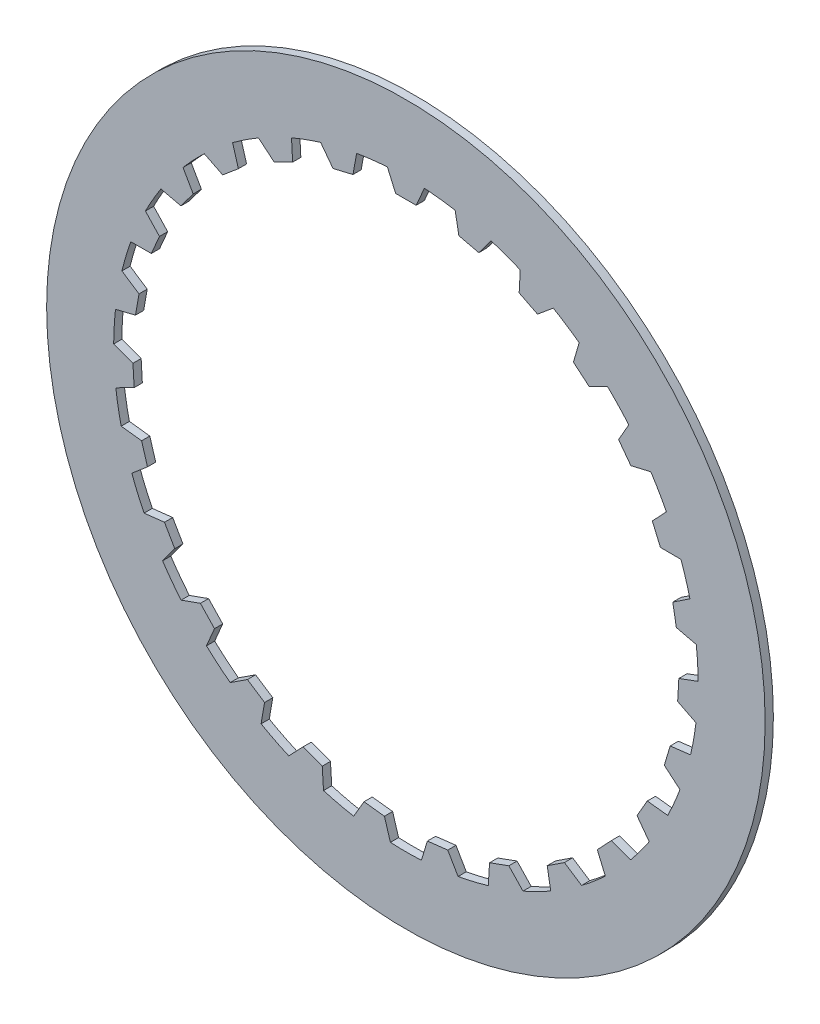
SolidWorks part; units mm, degrees
material "Plain Carbon Steel"
ref_plane "Front Plane" through (0, 0, 0) normal (0, 0, 1) x (1, 0, 0)
ref_plane "Top Plane" through (0, 0, 0) normal (0, 1, 0) x (1, 0, 0)
ref_plane "Right Plane" through (0, 0, 0) normal (1, 0, 0) x (0, 0, -1)
sketch "Sketch1" plane through (0, 0, 0) normal (0, 0, 1) x (1, 0, 0)
  line L0 (-3.429, 54.1205) -> (-1.905, 50.6286)
  line L1 (-1.905, 50.6286) -> (1.905, 50.6286)
  line L2 (1.905, 50.6286) -> (3.429, 54.1205)
  line L3 (0, 0) -> (0, 101.2571) construction
  line L4 (9.1445, 53.4524) -> (9.8221, 49.7032)
  line L5 (9.8221, 49.7032) -> (13.5294, 48.8245)
  line L6 (13.5294, 48.8245) -> (15.8176, 51.8709)
  line L7 (21.225, 49.9028) -> (21.0197, 46.0983)
  line L8 (21.0197, 46.0983) -> (24.4244, 44.3884)
  line L9 (24.4244, 44.3884) -> (27.3535, 46.8249)
  line L10 (32.1612, 43.6628) -> (31.0841, 40.0082)
  line L11 (31.0841, 40.0082) -> (34.0027, 37.5592)
  line L12 (34.0027, 37.5592) -> (37.4147, 39.2546)
  line L13 (41.3636, 35.069) -> (39.4728, 31.7613)
  line L14 (39.4728, 31.7613) -> (41.7479, 28.7052)
  line L15 (41.7479, 28.7052) -> (45.4589, 29.568)
  line L16 (48.3361, 24.5846) -> (45.7334, 21.8021)
  line L17 (45.7334, 21.8021) -> (47.2425, 18.3037)
  line L18 (47.2425, 18.3037) -> (51.0525, 18.2875)
  line L19 (52.7028, 12.7748) -> (49.5286, 10.6676)
  line L20 (49.5286, 10.6676) -> (50.1902, 6.9155)
  line L21 (50.1902, 6.9155) -> (53.8937, 6.021)
  line L22 (54.2283, 0.2764) -> (50.6537, -1.042)
  line L23 (50.6537, -1.042) -> (50.4321, -4.8456)
  line L24 (50.4321, -4.8456) -> (53.8295, -6.57)
  line L25 (52.8303, -12.237) -> (49.048, -12.6955)
  line L26 (49.048, -12.6955) -> (47.9553, -16.3454)
  line L27 (47.9553, -16.3454) -> (50.8634, -18.8069)
  line L28 (48.5842, -24.0906) -> (44.7981, -23.6645)
  line L29 (44.7981, -23.6645) -> (42.8931, -26.9641)
  line L30 (42.8931, -26.9641) -> (45.1552, -30.0298)
  line L31 (41.7189, -34.6456) -> (38.1332, -33.3578)
  line L32 (38.1332, -33.3578) -> (35.5186, -36.1291)
  line L33 (35.5186, -36.1291) -> (37.0127, -39.6339)
  line L34 (32.6046, -43.3327) -> (29.4125, -41.2527)
  line L35 (29.4125, -41.2527) -> (26.2292, -43.3464)
  line L36 (26.2292, -43.3464) -> (26.8748, -47.1013)
  line L37 (21.7325, -49.6838) -> (19.1061, -46.9237)
  line L38 (19.1061, -46.9237) -> (15.5259, -48.2268)
  line L39 (15.5259, -48.2268) -> (15.2881, -52.0294)
  line L40 (9.6888, -53.3565) -> (7.7697, -50.0651)
  line L41 (7.7697, -50.0651) -> (3.9855, -50.5074)
  line L42 (3.9855, -50.5074) -> (2.8772, -54.1526)
  line L43 (-2.8772, -54.1526) -> (-3.9855, -50.5074)
  line L44 (-3.9855, -50.5074) -> (-7.7697, -50.0651)
  line L45 (-7.7697, -50.0651) -> (-9.6888, -53.3565)
  line L46 (-15.2881, -52.0294) -> (-15.5259, -48.2268)
  line L47 (-15.5259, -48.2268) -> (-19.1061, -46.9237)
  line L48 (-19.1061, -46.9237) -> (-21.7325, -49.6838)
  line L49 (-26.8748, -47.1013) -> (-26.2292, -43.3464)
  line L50 (-26.2292, -43.3464) -> (-29.4125, -41.2527)
  line L51 (-29.4125, -41.2527) -> (-32.6046, -43.3327)
  line L52 (-37.0127, -39.6339) -> (-35.5186, -36.1291)
  line L53 (-35.5186, -36.1291) -> (-38.1332, -33.3578)
  line L54 (-38.1332, -33.3578) -> (-41.7189, -34.6456)
  line L55 (-45.1552, -30.0298) -> (-42.8931, -26.9641)
  line L56 (-42.8931, -26.9641) -> (-44.7981, -23.6645)
  line L57 (-44.7981, -23.6645) -> (-48.5842, -24.0906)
  line L58 (-50.8634, -18.8069) -> (-47.9553, -16.3454)
  line L59 (-47.9553, -16.3454) -> (-49.048, -12.6955)
  line L60 (-49.048, -12.6955) -> (-52.8303, -12.237)
  line L61 (-53.8295, -6.57) -> (-50.4321, -4.8456)
  line L62 (-50.4321, -4.8456) -> (-50.6537, -1.042)
  line L63 (-50.6537, -1.042) -> (-54.2283, 0.2764)
  line L64 (-53.8937, 6.021) -> (-50.1902, 6.9155)
  line L65 (-50.1902, 6.9155) -> (-49.5286, 10.6676)
  line L66 (-49.5286, 10.6676) -> (-52.7028, 12.7748)
  line L67 (-51.0525, 18.2875) -> (-47.2425, 18.3037)
  line L68 (-47.2425, 18.3037) -> (-45.7334, 21.8021)
  line L69 (-45.7334, 21.8021) -> (-48.3361, 24.5846)
  line L70 (-45.4589, 29.568) -> (-41.7479, 28.7052)
  line L71 (-41.7479, 28.7052) -> (-39.4728, 31.7613)
  line L72 (-39.4728, 31.7613) -> (-41.3636, 35.069)
  line L73 (-37.4147, 39.2546) -> (-34.0027, 37.5592)
  line L74 (-34.0027, 37.5592) -> (-31.0841, 40.0082)
  line L75 (-31.0841, 40.0082) -> (-32.1612, 43.6628)
  line L76 (-27.3535, 46.8249) -> (-24.4244, 44.3884)
  line L77 (-24.4244, 44.3884) -> (-21.0197, 46.0983)
  line L78 (-21.0197, 46.0983) -> (-21.225, 49.9028)
  line L79 (-15.8176, 51.8709) -> (-13.5294, 48.8245)
  line L80 (-13.5294, 48.8245) -> (-9.8221, 49.7032)
  line L81 (-9.8221, 49.7032) -> (-9.1445, 53.4524)
  circle A0 centre (0, 0) radius 66.675
  arc A1 (-15.8176, 51.8709) -> (-21.225, 49.9028) centre (0, 0) ccw
  arc A2 (-27.3535, 46.8249) -> (-32.1612, 43.6628) centre (0, 0) ccw
  arc A3 (-37.4147, 39.2546) -> (-41.3636, 35.069) centre (0, 0) ccw
  arc A4 (-45.4589, 29.568) -> (-48.3361, 24.5846) centre (0, 0) ccw
  arc A5 (-51.0525, 18.2875) -> (-52.7028, 12.7748) centre (0, 0) ccw
  arc A6 (-53.8937, 6.021) -> (-54.2283, 0.2764) centre (0, 0) ccw
  arc A7 (-53.8295, -6.57) -> (-52.8303, -12.237) centre (0, 0) ccw
  arc A8 (-50.8634, -18.8069) -> (-48.5842, -24.0906) centre (0, 0) ccw
  arc A9 (-45.1552, -30.0298) -> (-41.7189, -34.6456) centre (0, 0) ccw
  arc A10 (-37.0127, -39.6339) -> (-32.6046, -43.3327) centre (0, 0) ccw
  arc A11 (-26.8748, -47.1013) -> (-21.7325, -49.6838) centre (0, 0) ccw
  arc A12 (-15.2881, -52.0294) -> (-9.6888, -53.3565) centre (0, 0) ccw
  arc A13 (-2.8772, -54.1526) -> (2.8772, -54.1526) centre (0, 0) ccw
  arc A14 (9.6888, -53.3565) -> (15.2881, -52.0294) centre (0, 0) ccw
  arc A15 (21.7325, -49.6838) -> (26.8748, -47.1013) centre (0, 0) ccw
  arc A16 (41.7189, -34.6456) -> (45.1552, -30.0298) centre (0, 0) ccw
  arc A17 (32.6046, -43.3327) -> (37.0127, -39.6339) centre (0, 0) ccw
  arc A18 (48.5842, -24.0906) -> (50.8634, -18.8069) centre (0, 0) ccw
  arc A19 (52.8303, -12.237) -> (53.8295, -6.57) centre (0, 0) ccw
  arc A20 (54.2283, 0.2764) -> (53.8937, 6.021) centre (0, 0) ccw
  arc A21 (9.1445, 53.4524) -> (3.429, 54.1205) centre (0, 0) ccw
  arc A22 (21.225, 49.9028) -> (15.8176, 51.8709) centre (0, 0) ccw
  arc A23 (32.1612, 43.6628) -> (27.3535, 46.8249) centre (0, 0) ccw
  arc A24 (41.3636, 35.069) -> (37.4147, 39.2546) centre (0, 0) ccw
  arc A25 (48.3361, 24.5846) -> (45.4589, 29.568) centre (0, 0) ccw
  arc A26 (52.7028, 12.7748) -> (51.0525, 18.2875) centre (0, 0) ccw
  arc A27 (-3.429, 54.1205) -> (-9.1445, 53.4524) centre (0, 0) ccw
  point P8 (0, 50.6286)
  point P117 (0, 0)
  dimension "D1" = 133.35
  dimension "D2" = 108.458
  dimension "D3" = 3.81
  dimension "D4" = 3.429
  dimension "D5" = 3.429
  dimension "D6" = 3.81
  dimension "D7" = 27
extrude "Boss-Extrude1" add sketch "Sketch1" along normal blind 1.524
